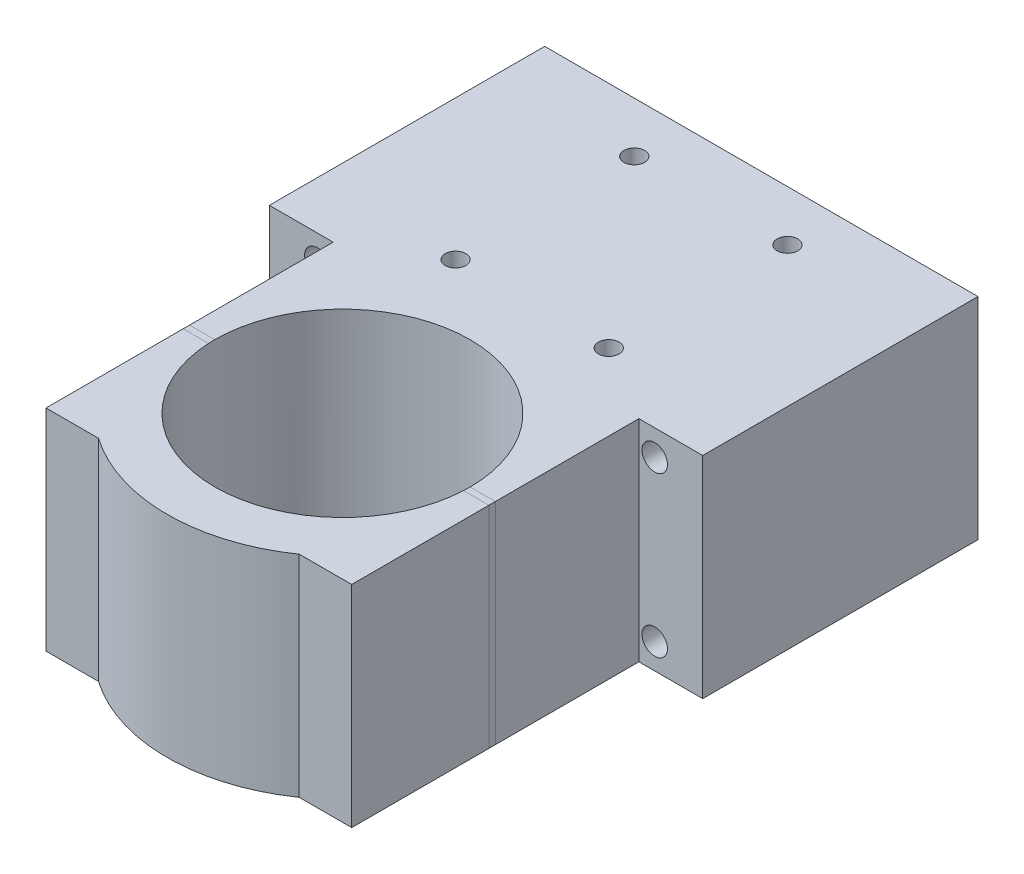
SolidWorks part; units mm, degrees
ref_plane "Front Plane" through (0, 0, 0) normal (0, 0, 1) x (1, 0, 0)
ref_plane "Top Plane" through (0, 0, 0) normal (0, 1, 0) x (1, 0, 0)
ref_plane "Right Plane" through (0, 0, 0) normal (1, 0, 0) x (0, 0, -1)
sketch "Sketch1" plane through (0, 0, 0) normal (0, 1, 0) x (1, 0, 0)
  line L0 (-47.3083, 17.816) -> (20.5912, 17.816)
  line L1 (20.5912, 17.816) -> (20.5912, 9.6753)
  line L2 (-47.3083, 17.816) -> (-47.3083, 9.6753)
  line L3 (-47.3083, 9.6753) -> (-37.3083, 9.6753)
  line L4 (10.5912, 9.6753) -> (20.5912, 9.6753)
  line L5 (-37.3083, 9.6753) -> (-37.3083, -35.3247)
  line L6 (10.5912, 9.6753) -> (10.5912, -35.3247)
  line L10 (-37.3083, -35.3247) -> (-29.0824, -35.3247)
  line L11 (10.5912, -35.3247) -> (2.3653, -35.3247)
  circle A0 centre (-13.3585, -12.8247) radius 18
  arc A1 (-29.0824, -35.3247) -> (2.3653, -35.3247) centre (-13.3585, -12.8247) ccw
  dimension "D1" = 45
  dimension "D2" = 45
  dimension "D5" = 10
  dimension "D6" = 10
  dimension "D7" = 67.8995
extrude "Boss-Extrude3" add sketch "Sketch1" along normal blind 33 contours A0 | L5 L10 A1 L11 L6 L4 L1 L0 L2 L3
sketch "Sketch8" plane through (-37.3083, 0, 0) normal (-1, 0, 0) x (0, 0, 1)
  line L0 (12.8247, 33) -> (12.8247, 0)
  line L1 (-9.6753, 33) -> (35.3247, 33) construction
  line L2 (-9.6753, 0) -> (35.3247, 0) construction
  line L3 (13.8247, 33) -> (13.8247, 0)
  dimension "D1" = 1
split line "Split Line1"
sketch "Sketch10" plane through (0, 33, 0) normal (0, 1, 0) x (1, 0, 0)
  line L0 (-37.3083, -12.8247) -> (-31.3585, -12.8247)
  line L1 (4.6415, -12.8247) -> (10.5912, -12.8247)
  line L2 (10.5912, 9.6753) -> (10.5912, -35.3247) construction
  line L3 (-37.3083, -13.8247) -> (-31.3307, -13.8247)
  line L4 (10.5912, -13.8247) -> (4.6137, -13.8247)
  circle A0 centre (-13.3585, -12.8247) radius 18 construction
split line "Split Line2"
sketch "Sketch11" plane through (10.5912, 0, 0) normal (1, 0, 0) x (0, 0, -1)
  line L0 (-12.8247, 33) -> (-12.8247, 0)
  line L1 (9.6753, 0) -> (-35.3247, 0) construction
  line L2 (-13.8247, 33) -> (-13.8247, 0)
split line "Split Line3"
sketch "Sketch12" plane through (0, 0, -17.816) normal (0, 0, -1) x (-1, 0, 0)
  line L0 (47.3083, 0) -> (-20.5912, 0) construction
  line L1 (47.3083, 33) -> (47.3083, 0) construction
  line L3 (47.3083, 33) -> (-20.5912, 33) construction
  line L4 (-20.5912, 33) -> (-20.5912, 0) construction
  circle A0 centre (39.7883, 4) radius 2
  circle A1 centre (39.7883, 29) radius 2
  circle A2 centre (-13.0712, 29) radius 2
  circle A3 centre (-13.0712, 4) radius 2
  dimension "D1" = 4
  dimension "D2" = 7.52
  dimension "D3" = 7.52
  dimension "D4" = 4
  dimension "D5" = 7.52
  dimension "D6" = 7.52
  dimension "D7" = 4
extrude "Cut-Extrude1" cut sketch "Sketch12" against normal blind 10
sketch "Sketch13" plane through (0, 33, 0) normal (0, 1, 0) x (1, 0, 0)
  line L0 (20.5912, 17.816) -> (20.5912, 9.6753) construction
  line L1 (-47.3083, 17.816) -> (20.5912, 17.816)
  line L2 (-47.3083, 17.816) -> (-47.3083, 52.816)
  line L3 (-47.3083, 52.816) -> (20.5912, 52.816)
  line L4 (20.5912, 17.816) -> (20.5912, 52.816)
  dimension "D1" = 0
  dimension "D2" = 35
extrude "Boss-Extrude4" add sketch "Sketch13" against normal blind 33
sketch "Sketch14" plane through (0, 33, 0) normal (0, 1, 0) x (1, 0, 0)
  line L3 (-47.3083, 52.816) -> (-47.3083, 9.6753) construction
  circle A0 centre (-25.3583, 16.9) radius 1.62
  circle A1 centre (-1.3583, 16.9) radius 1.62
  circle A2 centre (-25.3583, 44.9) radius 1.62
  circle A3 centre (-1.3583, 44.9) radius 1.62
  dimension "D4" = 21.95
  dimension "D5" = 3.24
  dimension "D6" = 3.24
  dimension "D7" = 3.24
  dimension "D8" = 3.24
  dimension "D1" = 28
  dimension "D2" = 28
  dimension "D3" = 24
extrude "Cut-Extrude2" cut sketch "Sketch14" against normal blind 10
sketch "Sketch15" plane through (0, 0, 0) normal (0, -1, 0) x (1, 0, 0)
  circle A0 centre (-13.3585, 12.8247) radius 20
  dimension "D1" = 40
extrude "Cut-Extrude3" cut sketch "Sketch15" against normal through all
